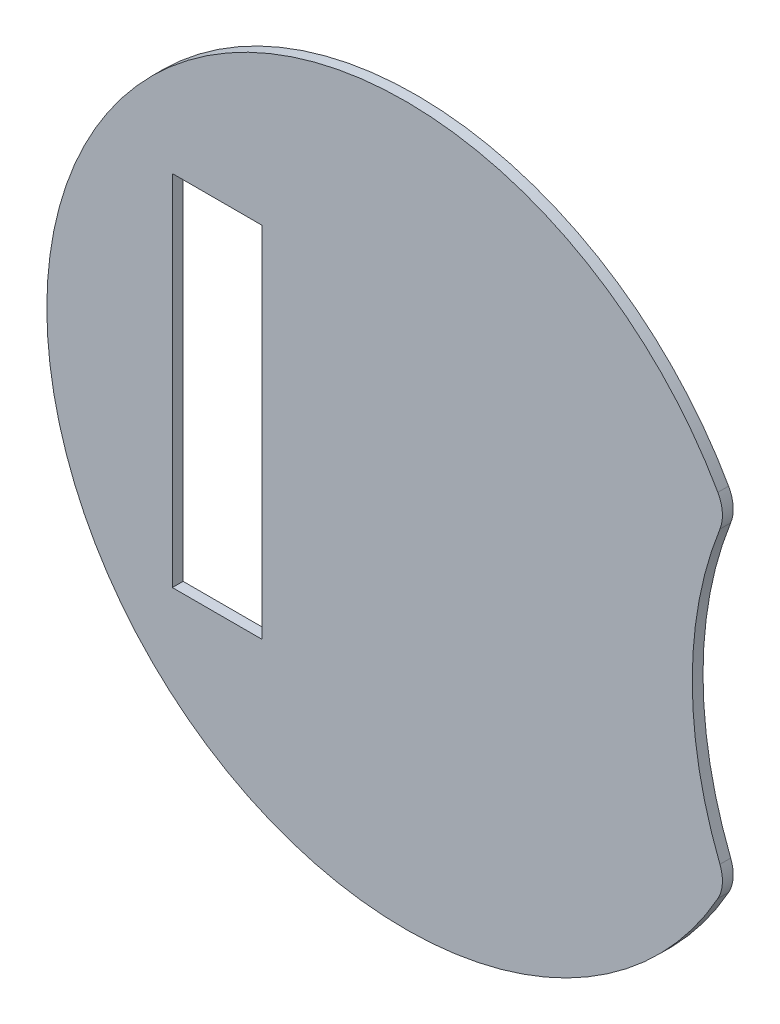
SolidWorks part; units mm, degrees
ref_plane "Alzado" through (0, 0, 0) normal (0, 0, 1) x (1, 0, 0)
ref_plane "Planta" through (0, 0, 0) normal (0, 1, 0) x (1, 0, 0)
ref_plane "Vista lateral" through (0, 0, 0) normal (1, 0, 0) x (0, 0, -1)
sketch "Croquis1" plane through (0, 0, 0) normal (0, 0, 1) x (1, 0, 0)
  circle A0 centre (0, 0) radius 100
  dimension "D1" = 200
extrude "Saliente-Extruir1" add sketch "Croquis1" along normal blind 3
sketch "Croquis3" plane through (0, 0, 3) normal (0, 0, 1) x (1, 0, 0)
  line L0 (0, 0) -> (190, 0) construction
  circle A0 centre (190, 0) radius 110
  dimension "D1" = 220
  dimension "D2" = 190
extrude "Cortar-Extruir1" cut sketch "Croquis3" against normal blind 3
fillet "Redondeo1" radius 10 2 edges at (89.4737, -44.6594, 1.5) (89.4737, 44.6594, 1.5)
sketch "Croquis4" plane through (0, 0, 0) normal (0, 0, -1) x (-1, 0, 0)
  line L1 (40, 50) -> (65, 50)
  line L2 (40, 50) -> (40, -50)
  line L3 (40, -50) -> (65, -50)
  line L4 (65, 50) -> (65, -50)
  arc A0 (-87.1345, -49.0671) -> (-87.1345, 49.0671) centre (0, 0) ccw construction
  dimension "D1" = 100
  dimension "D2" = 25
  dimension "D3" = 50
  dimension "D4" = 65
extrude "Cortar-Extruir2" cut sketch "Croquis4" against normal through all
